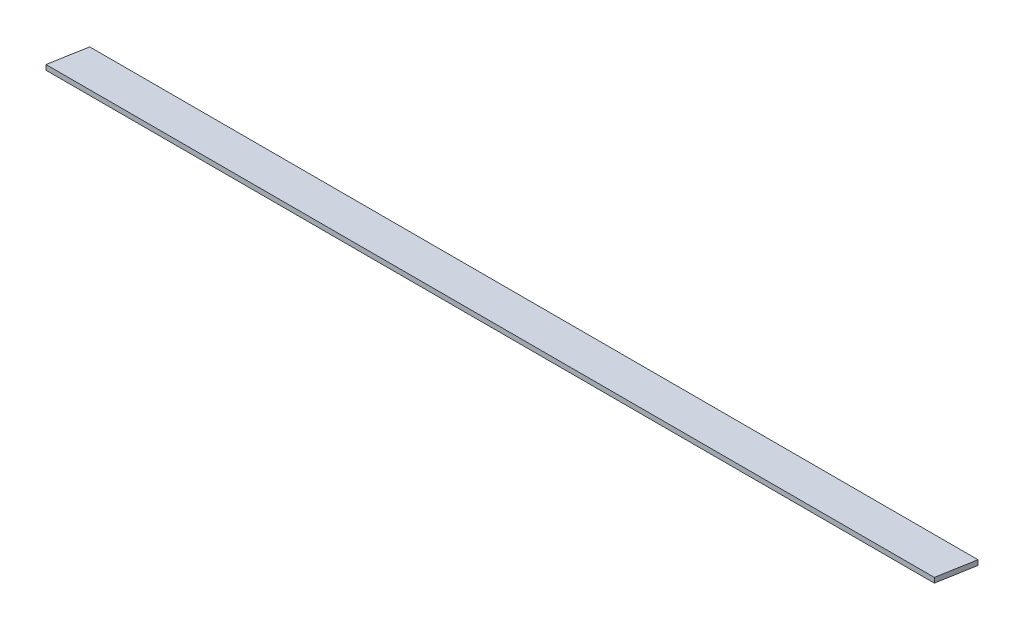
SolidWorks part; units mm, degrees
ref_plane "Front Plane" through (0, 0, 0) normal (0, 0, 1) x (1, 0, 0)
ref_plane "Top Plane" through (0, 0, 0) normal (0, 1, 0) x (1, 0, 0)
ref_plane "Right Plane" through (0, 0, 0) normal (1, 0, 0) x (0, 0, -1)
sketch "Sketch1" plane through (0, 0, 0) normal (0, 1, 0) x (1, 0, 0)
  line L1 (-1143, 44.45) -> (1143, 44.45)
  line L2 (-1143, 44.45) -> (-1143, -44.45)
  line L3 (-1143, -44.45) -> (1143, -44.45)
  line L4 (1143, 44.45) -> (1143, -44.45)
  line L5 (-1143, 44.45) -> (1143, -44.45) construction
  line L6 (-1143, -44.45) -> (1143, 44.45) construction
  point P0 (0, 0)
  dimension "D1" = 88.9
  dimension "D2" = 2286
extrude "Boss-Extrude1" add sketch "Sketch1" along normal mid plane 11.9062
hole_wizard "1/4 Clearance Hole1" [suppressed] positions "Sketch2" profile "Sketch3" hole size "1/4" standard "ANSI Inch"
sketch "Sketch2" plane through (0, 5.9531, 0) normal (0, 1, 0) x (1, 0, 0)
  line L0 (-1143, -44.45) -> (1143, -44.45) construction
  line L1 (1143, -44.45) -> (1143, 44.45) construction
  point P0 (1016, 0)
  point P7 (1038.4506, 22.4506)
  point P9 (1031.2664, -27.8388)
  point P11 (-970.8817, 0)
  point P13 (-993.3323, -22.4506)
  point P15 (-986.1481, 27.8388)
  dimension "D1" = 44.45
  dimension "D2" = 127
sketch "Sketch3" plane through (1016, 5.9531, 0) normal (1, 0, 0) x (0, 0, 1)
  line L0 (0, 0) -> (0, 11.9062)
  line L1 (0, 11.9062) -> (3.3782, 11.9062)
  line L2 (3.3782, 11.9062) -> (3.3782, 0)
  line L5 (3.3782, 0) -> (0, 0)
  line L11 (0, -6.35) -> (0, 107.95) construction
  dimension "Thru Hole Dia." = 6.7564
  dimension "Thru Hole Depth" = 11.9062
sketch "Sketch4" plane through (0, 5.9531, 0) normal (0, 1, 0) x (1, 0, 0)
  line L0 (-1035.2495, 44.45) -> (-1050.925, -44.45)
  line L1 (1143, 44.45) -> (-1143, 44.45) construction
  line L2 (-1143, -44.45) -> (1143, -44.45) construction
  line L3 (-1050.925, -44.45) -> (-1143, -44.45)
  line L4 (-1143, -44.45) -> (-1143, 44.45)
  line L5 (-1143, 44.45) -> (-1143, -44.45) construction
  line L6 (-1143, 44.45) -> (-1035.2495, 44.45)
  line L7 (1090.413, 44.45) -> (1074.7375, -44.45)
  line L8 (1074.7375, -44.45) -> (1143, -44.45)
  line L9 (1143, -44.45) -> (1143, 44.45)
  line L10 (1143, 44.45) -> (1090.413, 44.45)
  line L11 (1143, -44.45) -> (1143, 44.45) construction
  dimension "D1" = 88.9
  dimension "D2" = 80
  dimension "D3" = 80
  dimension "D4" = 92.075
  dimension "D5" = 68.2625
extrude "Cut-Extrude1" cut sketch "Sketch4" against normal through all
sketch "Sketch5" plane through (0, 5.9531, 0) normal (0, 1, 0) x (1, 0, 0)
  line L0 (1082.5752, 0) -> (1067.3385, 0) construction
  line L1 (1090.413, 44.45) -> (1074.7375, -44.45) construction
  line L2 (1062.9009, 2.5507) -> (1083.025, 2.5507)
  line L6 (1081.9509, -3.5407) -> (1083.025, 2.5507)
  line L7 (1062.9009, -3.5407) -> (1081.9509, -3.5407)
  line L8 (-1043.0873, 0) -> (-1024.5971, 0) construction
  line L9 (-1050.925, -44.45) -> (-1035.2495, 44.45) construction
  line L10 (-1024.5971, 3.175) -> (-1042.5274, 3.175)
  line L13 (-1042.5274, 3.175) -> (-1043.6471, -3.175)
  line L14 (-1043.6471, -3.175) -> (-1024.5971, -3.175)
  line L15 (-1050.925, -44.45) -> (1074.7375, -44.45) construction
  arc A0 (1062.9009, 2.5507) -> (1062.9009, -3.5407) centre (1062.9009, -0.495) ccw
  arc A1 (-1024.5971, -3.175) -> (-1024.5971, 3.175) centre (-1024.5971, 0) ccw
  line M9 (-1035.2495, 44.45) -> (-1050.925, -44.45)
  line M11 (1074.7375, -44.45) -> (1090.413, 44.45)
  dimension "D1" = 3.0457
  dimension "D3" = 6.35
  dimension "D2" = 19.05
  dimension "D4" = 19.05
extrude "Cut-Extrude2" [suppressed] cut sketch "Sketch5" against normal through all contours L2 A0 L7 M11 | L14 A1 L10 M9
